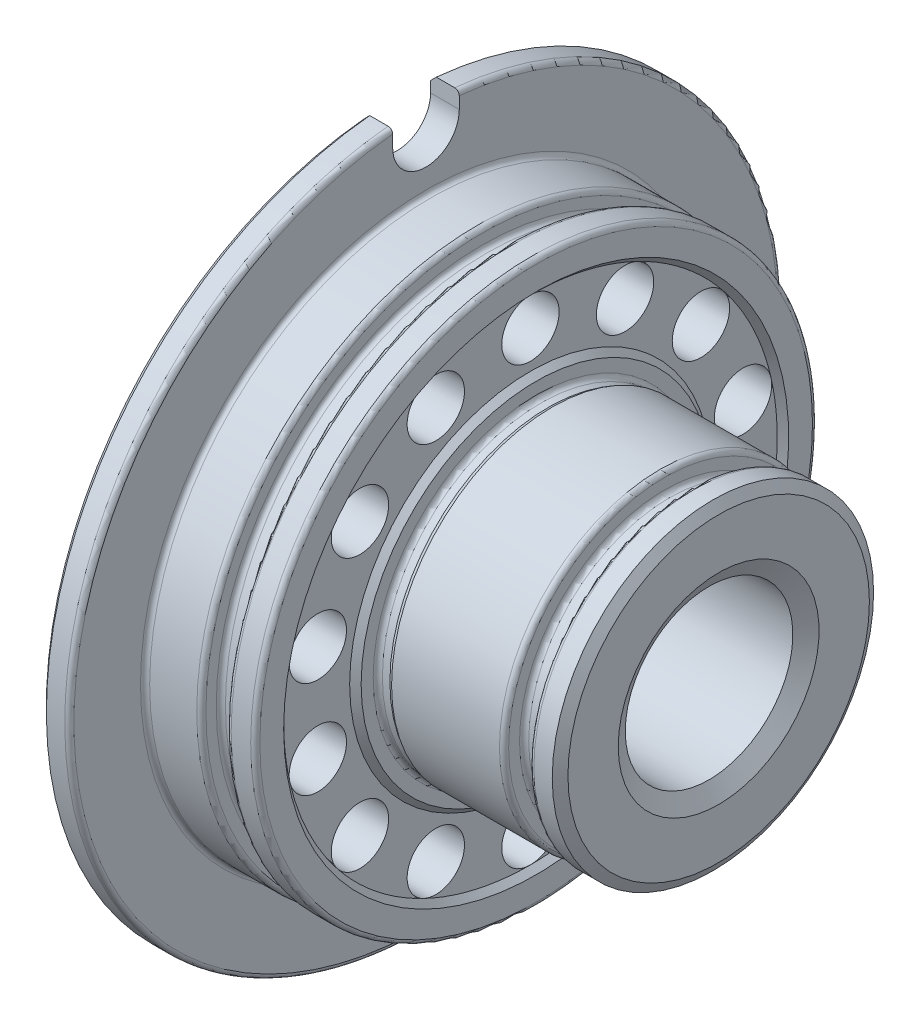
SolidWorks part; units mm, degrees
material "4140 H-T"
ref_plane "Front Plane" through (0, 0, 0) normal (0, 0, 1) x (1, 0, 0)
ref_plane "Top Plane" through (0, 0, 0) normal (0, 1, 0) x (1, 0, 0)
ref_plane "Right Plane" through (0, 0, 0) normal (1, 0, 0) x (0, 0, -1)
sketch "Sketch1" plane through (0, 0, 0) normal (0, 0, 1) x (1, 0, 0)
  line L0 (0, 0) -> (33.2077, 0) construction
  line L1 (0.4, 7.3) -> (27.1628, 7.3)
  line L2 (0.4, 7.3) -> (0.4, 13.5)
  line L3 (13.5, 14) -> (13.1536, 13.8)
  line L4 (0, 13.9) -> (0, 30.575)
  line L5 (0.5, 31.075) -> (2.1, 31.075)
  line L6 (2.5, 30.675) -> (2.5, 24.875)
  line L7 (2.9, 24.475) -> (7, 24.475)
  line L8 (7.4, 24.075) -> (7.4, 23.175)
  line L9 (7.8, 22.775) -> (9.2, 22.775)
  line L10 (9.6, 23.175) -> (9.6, 24.075)
  line L11 (10, 24.475) -> (11.7, 24.475)
  line L12 (12.1, 24.075) -> (12.1, 22)
  line L13 (13.5, 14) -> (22.9, 14)
  line L14 (23.3, 12.65) -> (23.3, 13.6)
  line L15 (23.7, 12.25) -> (25.1, 12.25)
  line L16 (25.5, 12.65) -> (25.5, 13.6)
  line L17 (25.9, 14) -> (27.5, 14)
  line L18 (28, 13.134) -> (28, 8.75)
  line L19 (0.4, 13.5) -> (0, 13.9)
  line L20 (13.1536, 13.8) -> (12.5, 13.8)
  line L21 (12.1, 15.25) -> (12.1, 14.2)
  line L22 (12.1, 15.25) -> (11.6, 15.75)
  line L23 (11.6, 21.5) -> (11.6, 15.75)
  line L24 (12.1, 22) -> (11.6, 21.5)
  line L26 (0, 30.575) -> (0.5, 31.075)
  line L27 (28, 8.75) -> (27.1628, 7.3)
  line L28 (27.5, 14) -> (28, 13.134)
  arc A0 (12.1, 14.2) -> (12.5, 13.8) centre (12.5, 14.2) ccw
  arc A1 (7.4, 23.175) -> (7.8, 22.775) centre (7.8, 23.175) ccw
  arc A2 (9.2, 22.775) -> (9.6, 23.175) centre (9.2, 23.175) ccw
  arc A3 (23.3, 12.65) -> (23.7, 12.25) centre (23.7, 12.65) ccw
  arc A4 (25.1, 12.25) -> (25.5, 12.65) centre (25.1, 12.65) ccw
  arc A5 (2.1, 31.075) -> (2.5, 30.675) centre (2.1, 30.675) cw
  arc A6 (2.5, 24.875) -> (2.9, 24.475) centre (2.9, 24.875) ccw
  arc A7 (11.7, 24.475) -> (12.1, 24.075) centre (11.7, 24.075) cw
  arc A8 (7, 24.475) -> (7.4, 24.075) centre (7, 24.075) cw
  arc A9 (9.6, 24.075) -> (10, 24.475) centre (10, 24.075) cw
  arc A10 (22.9, 14) -> (23.3, 13.6) centre (22.9, 13.6) cw
  arc A11 (25.5, 13.6) -> (25.9, 14) centre (25.9, 13.6) cw
  point P33 (7.4, 22.775)
  point P36 (9.6, 22.775)
  point P39 (23.3, 12.25)
  point P42 (25.5, 12.25)
  point P48 (12.1, 24.475)
  point P53 (9.6, 24.475)
  point P58 (25.5, 14)
  dimension "D28" = 30.5
  dimension "D30" = 0.4
  dimension "D31" = 0.4
  dimension "D32" = 0.4
  dimension "D17" = 0.4
  dimension "D1" = 14.6
  dimension "D2" = 27
  dimension "D3" = 0.4
  dimension "D4" = 45
  dimension "D5" = 62.15
  dimension "D6" = 0.5
  dimension "D7" = 48.95
  dimension "D8" = 2.2
  dimension "D9" = 2.2
  dimension "D10" = 12.1
  dimension "D11" = 45.55
  dimension "D12" = 2.5
  dimension "D13" = 28
  dimension "D14" = 0.5
  dimension "D15" = 44
  dimension "D16" = 0.2
  dimension "D18" = 24.5
  dimension "D19" = 2.5
  dimension "D20" = 28
  dimension "D21" = 30
  dimension "D22" = 45
  dimension "D23" = 2.5
  dimension "D24" = 60
  dimension "D25" = 0.5
  dimension "D26" = 17.5
  dimension "D27" = 30
  dimension "D29" = 45
  dimension "D33" = 45
  dimension "D34" = 14.5
revolve "Revolve1" add sketch "Sketch1" angle 360 about L0
sketch "Sketch2" plane through (0, 0, 0) normal (-1, 0, 0) x (0, 0, 1)
  line L0 (0, 0) -> (37.309, 0) construction
  line L1 (0, 0) -> (0, 29.0181) construction
  circle A0 centre (0, 19) radius 2.5
  circle A1 centre (0, -19) radius 2.5
  dimension "D1" = 5
  dimension "D2" = 38
extrude "Extrude1" cut sketch "Sketch2" against normal up to next
sketch "Sketch3" plane through (0, 0, 0) normal (-1, 0, 0) x (0, 0, 1)
  line L0 (0, 0) -> (0, 32.8515) construction
  line L1 (2.9, 29.5) -> (2.9, 30.9394)
  line L2 (-2.9, 29.5) -> (-2.9, 30.9394)
  arc A0 (-2.9, 29.5) -> (2.9, 29.5) centre (0, 29.5) ccw
  circle A1 centre (0, 0) radius 31.075 construction
  arc A2 (2.9, 30.9394) -> (-2.9, 30.9394) centre (0, 0) ccw
  circle A3 centre (0, 0) radius 7.3 construction
  dimension "D2" = 29.5
  dimension "D1" = 5.8
extrude "Extrude2" cut sketch "Sketch3" against normal up to next
pattern_circular "CirPattern1" count 7 over 360 about axis through (0, 0, 0) along (1, 0, 0) of "Extrude1"
